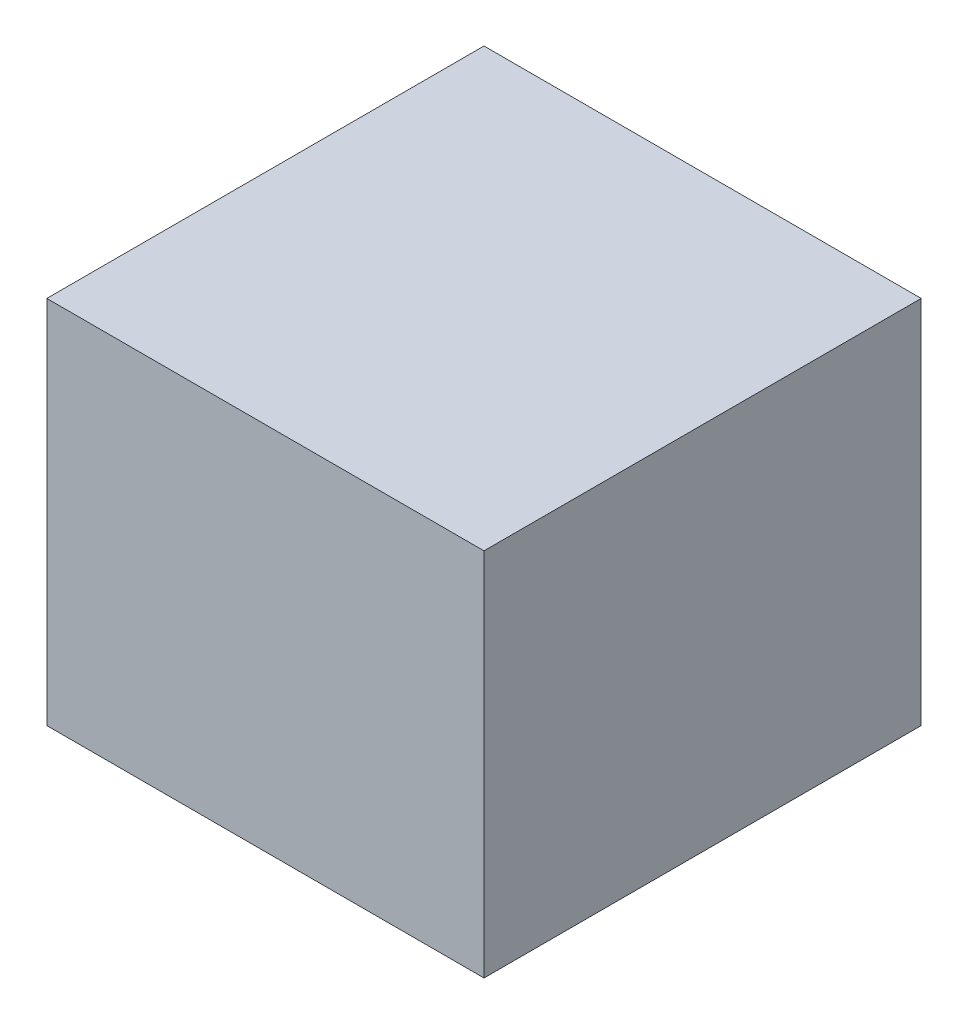
SolidWorks part; units mm, degrees
ref_plane "Front Plane" through (0, 0, 0) normal (0, 0, 1) x (1, 0, 0)
ref_plane "Top Plane" through (0, 0, 0) normal (0, 1, 0) x (1, 0, 0)
ref_plane "Right Plane" through (0, 0, 0) normal (1, 0, 0) x (0, 0, -1)
sketch "Sketch1" plane through (0, 0, 0) normal (0, 1, 0) x (1, 0, 0)
  line L1 (0, 0) -> (330.2, 0)
  line L2 (0, 0) -> (0, 330.2)
  line L3 (0, 330.2) -> (330.2, 330.2)
  line L4 (330.2, 0) -> (330.2, 330.2)
  dimension "D1" = 330.2
extrude "Boss-Extrude1" add sketch "Sketch1" along normal blind 279.4
